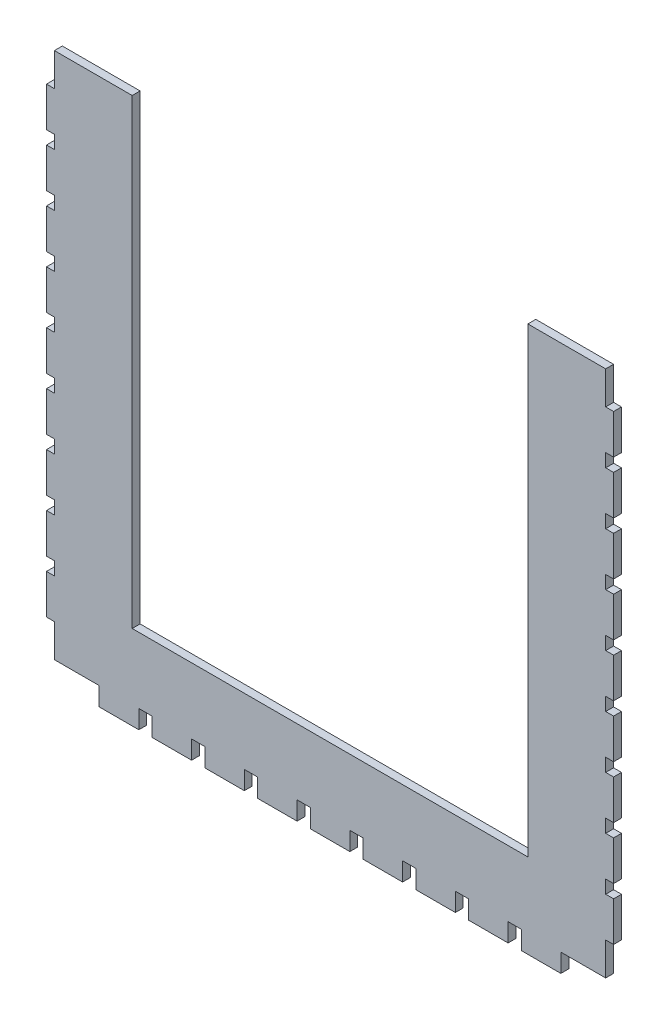
SolidWorks part; units mm, degrees
material "Nickel"
ref_plane "Front Plane" through (0, 0, 0) normal (0, 0, 1) x (1, 0, 0)
ref_plane "Top Plane" through (0, 0, 0) normal (0, 1, 0) x (1, 0, 0)
ref_plane "Right Plane" through (0, 0, 0) normal (1, 0, 0) x (0, 0, -1)
sketch "Sketch1" plane through (0, 0, 0) normal (0, 0, 1) x (1, 0, 0)
  line L0 (-104.5, 100) -> (-104.5, -100)
  line L3 (-104.5, 100) -> (104.5, 100)
  line L4 (104.5, -100) -> (104.5, 100)
  line L5 (-104.5, -100) -> (104.5, -100)
  line L6 (0, 100) -> (0, -100) construction
  line L7 (-104.5, 0) -> (104.5, 0) construction
  line L8 (107.5, 0) -> (104.5, 0) construction
  line L9 (-75, 100) -> (75, 100)
  line L10 (-75, 100) -> (-75, -75)
  line L11 (-75, -75) -> (75, -75)
  line L12 (75, 100) -> (75, -75)
  line L15 (104.5, 7.5) -> (107.5, 7.5)
  line L16 (104.5, 7.5) -> (104.5, -7.5)
  line L17 (104.5, -7.5) -> (107.5, -7.5)
  line L18 (107.5, 7.5) -> (107.5, -7.5)
  line L19 (106, 7.5) -> (106, -7.5) construction
  line L20 (104.5, -12.5) -> (104.5, -27.5)
  line L21 (104.5, -12.5) -> (107.5, -12.5)
  line L22 (107.5, -12.5) -> (107.5, -27.5)
  line L23 (104.5, -27.5) -> (107.5, -27.5)
  line L24 (104.5, -32.5) -> (104.5, -47.5)
  line L25 (104.5, -32.5) -> (107.5, -32.5)
  line L26 (107.5, -32.5) -> (107.5, -47.5)
  line L27 (104.5, -47.5) -> (107.5, -47.5)
  line L28 (104.5, -52.5) -> (104.5, -67.5)
  line L29 (104.5, -52.5) -> (107.5, -52.5)
  line L30 (107.5, -52.5) -> (107.5, -67.5)
  line L31 (104.5, -67.5) -> (107.5, -67.5)
  line L32 (104.5, -72.5) -> (104.5, -87.5)
  line L33 (104.5, -72.5) -> (107.5, -72.5)
  line L34 (107.5, -72.5) -> (107.5, -87.5)
  line L35 (104.5, -87.5) -> (107.5, -87.5)
  line L36 (104.5, 27.5) -> (104.5, 12.5)
  line L37 (104.5, 27.5) -> (107.5, 27.5)
  line L38 (107.5, 27.5) -> (107.5, 12.5)
  line L39 (104.5, 12.5) -> (107.5, 12.5)
  line L40 (104.5, 47.5) -> (104.5, 32.5)
  line L41 (104.5, 47.5) -> (107.5, 47.5)
  line L42 (107.5, 47.5) -> (107.5, 32.5)
  line L43 (104.5, 32.5) -> (107.5, 32.5)
  line L44 (104.5, 67.5) -> (104.5, 52.5)
  line L45 (104.5, 67.5) -> (107.5, 67.5)
  line L46 (107.5, 67.5) -> (107.5, 52.5)
  line L47 (104.5, 52.5) -> (107.5, 52.5)
  line L48 (104.5, 87.5) -> (104.5, 72.5)
  line L49 (104.5, 87.5) -> (107.5, 87.5)
  line L50 (107.5, 87.5) -> (107.5, 72.5)
  line L51 (104.5, 72.5) -> (107.5, 72.5)
  line L52 (-104.5, -32.5) -> (-107.5, -32.5)
  line L53 (-107.5, -32.5) -> (-107.5, -47.5)
  line L54 (-104.5, -47.5) -> (-107.5, -47.5)
  line L55 (-104.5, -32.5) -> (-104.5, -47.5)
  line L56 (-104.5, -52.5) -> (-107.5, -52.5)
  line L57 (-107.5, -52.5) -> (-107.5, -67.5)
  line L58 (-104.5, -67.5) -> (-107.5, -67.5)
  line L59 (-104.5, -52.5) -> (-104.5, -67.5)
  line L60 (-104.5, 87.5) -> (-107.5, 87.5)
  line L61 (-107.5, 87.5) -> (-107.5, 72.5)
  line L62 (-104.5, 72.5) -> (-107.5, 72.5)
  line L63 (-104.5, 87.5) -> (-104.5, 72.5)
  line L64 (-104.5, 67.5) -> (-107.5, 67.5)
  line L65 (-107.5, 67.5) -> (-107.5, 52.5)
  line L66 (-104.5, 52.5) -> (-107.5, 52.5)
  line L67 (-104.5, 67.5) -> (-104.5, 52.5)
  line L68 (-104.5, 47.5) -> (-107.5, 47.5)
  line L69 (-107.5, 47.5) -> (-107.5, 32.5)
  line L70 (-104.5, 32.5) -> (-107.5, 32.5)
  line L71 (-104.5, 47.5) -> (-104.5, 32.5)
  line L72 (-104.5, 27.5) -> (-107.5, 27.5)
  line L73 (-107.5, 27.5) -> (-107.5, 12.5)
  line L74 (-104.5, 12.5) -> (-107.5, 12.5)
  line L75 (-104.5, 27.5) -> (-104.5, 12.5)
  line L76 (-104.5, -12.5) -> (-107.5, -12.5)
  line L77 (-107.5, -12.5) -> (-107.5, -27.5)
  line L78 (-104.5, -27.5) -> (-107.5, -27.5)
  line L79 (-104.5, -12.5) -> (-104.5, -27.5)
  line L80 (-104.5, -7.5) -> (-107.5, -7.5)
  line L81 (-107.5, 7.5) -> (-107.5, -7.5)
  line L82 (-104.5, 7.5) -> (-107.5, 7.5)
  line L83 (-104.5, 7.5) -> (-104.5, -7.5)
  line L84 (-104.5, -87.5) -> (-107.5, -87.5)
  line L85 (-107.5, -72.5) -> (-107.5, -87.5)
  line L86 (-104.5, -72.5) -> (-107.5, -72.5)
  line L87 (-104.5, -72.5) -> (-104.5, -87.5)
  line L88 (0, -100) -> (0, -107) construction
  line L89 (-7.5, -100) -> (7.5, -100)
  line L90 (-7.5, -100) -> (-7.5, -107)
  line L91 (-7.5, -107) -> (7.5, -107)
  line L92 (7.5, -100) -> (7.5, -107)
  line L93 (12.5, -100) -> (12.5, -107)
  line L94 (-7.5, -103.5) -> (7.5, -103.5) construction
  line L95 (12.5, -100) -> (27.5, -100)
  line L96 (27.5, -100) -> (27.5, -107)
  line L97 (12.5, -107) -> (27.5, -107)
  line L98 (32.5, -100) -> (32.5, -107)
  line L99 (32.5, -100) -> (47.5, -100)
  line L100 (47.5, -100) -> (47.5, -107)
  line L101 (32.5, -107) -> (47.5, -107)
  line L102 (52.5, -100) -> (52.5, -107)
  line L103 (52.5, -100) -> (67.5, -100)
  line L104 (67.5, -100) -> (67.5, -107)
  line L105 (52.5, -107) -> (67.5, -107)
  line L106 (72.5, -100) -> (72.5, -107)
  line L107 (72.5, -100) -> (87.5, -100)
  line L108 (87.5, -100) -> (87.5, -107)
  line L109 (72.5, -107) -> (87.5, -107)
  line L110 (-7.5, -100) -> (-7.5, -107)
  line L111 (-7.5, -100) -> (7.5, -100)
  line L112 (7.5, -100) -> (7.5, -107)
  line L113 (-7.5, -107) -> (7.5, -107)
  line L114 (12.5, -100) -> (12.5, -107)
  line L115 (12.5, -100) -> (27.5, -100)
  line L116 (27.5, -100) -> (27.5, -107)
  line L117 (12.5, -107) -> (27.5, -107)
  line L118 (32.5, -100) -> (32.5, -107)
  line L119 (32.5, -100) -> (47.5, -100)
  line L120 (47.5, -100) -> (47.5, -107)
  line L121 (32.5, -107) -> (47.5, -107)
  line L122 (52.5, -100) -> (52.5, -107)
  line L123 (52.5, -100) -> (67.5, -100)
  line L124 (67.5, -100) -> (67.5, -107)
  line L125 (52.5, -107) -> (67.5, -107)
  line L126 (-27.5, -100) -> (-27.5, -107)
  line L127 (-27.5, -100) -> (-12.5, -100)
  line L128 (-12.5, -100) -> (-12.5, -107)
  line L129 (-27.5, -107) -> (-12.5, -107)
  line L130 (-7.5, -100) -> (-7.5, -107)
  line L131 (-7.5, -100) -> (7.5, -100)
  line L132 (7.5, -100) -> (7.5, -107)
  line L133 (-7.5, -107) -> (7.5, -107)
  line L134 (12.5, -100) -> (12.5, -107)
  line L135 (12.5, -100) -> (27.5, -100)
  line L136 (27.5, -100) -> (27.5, -107)
  line L137 (12.5, -107) -> (27.5, -107)
  line L138 (32.5, -100) -> (32.5, -107)
  line L139 (32.5, -100) -> (47.5, -100)
  line L140 (47.5, -100) -> (47.5, -107)
  line L141 (32.5, -107) -> (47.5, -107)
  line L142 (-47.5, -100) -> (-47.5, -107)
  line L143 (-47.5, -100) -> (-32.5, -100)
  line L144 (-32.5, -100) -> (-32.5, -107)
  line L145 (-47.5, -107) -> (-32.5, -107)
  line L146 (-27.5, -100) -> (-27.5, -107)
  line L147 (-27.5, -100) -> (-12.5, -100)
  line L148 (-12.5, -100) -> (-12.5, -107)
  line L149 (-27.5, -107) -> (-12.5, -107)
  line L150 (-7.5, -100) -> (-7.5, -107)
  line L151 (-7.5, -100) -> (7.5, -100)
  line L152 (7.5, -100) -> (7.5, -107)
  line L153 (-7.5, -107) -> (7.5, -107)
  line L154 (12.5, -100) -> (12.5, -107)
  line L155 (12.5, -100) -> (27.5, -100)
  line L156 (27.5, -100) -> (27.5, -107)
  line L157 (12.5, -107) -> (27.5, -107)
  line L158 (-67.5, -100) -> (-67.5, -107)
  line L159 (-67.5, -100) -> (-52.5, -100)
  line L160 (-52.5, -100) -> (-52.5, -107)
  line L161 (-67.5, -107) -> (-52.5, -107)
  line L162 (-47.5, -100) -> (-47.5, -107)
  line L163 (-47.5, -100) -> (-32.5, -100)
  line L164 (-32.5, -100) -> (-32.5, -107)
  line L165 (-47.5, -107) -> (-32.5, -107)
  line L166 (-27.5, -100) -> (-27.5, -107)
  line L167 (-27.5, -100) -> (-12.5, -100)
  line L168 (-12.5, -100) -> (-12.5, -107)
  line L169 (-27.5, -107) -> (-12.5, -107)
  line L170 (-7.5, -100) -> (-7.5, -107)
  line L171 (-7.5, -100) -> (7.5, -100)
  line L172 (7.5, -100) -> (7.5, -107)
  line L173 (-7.5, -107) -> (7.5, -107)
  line L174 (-27.5, -100) -> (-27.5, -107)
  line L175 (-27.5, -100) -> (-12.5, -100)
  line L176 (-12.5, -100) -> (-12.5, -107)
  line L177 (-27.5, -107) -> (-12.5, -107)
  line L178 (-47.5, -100) -> (-47.5, -107)
  line L179 (-47.5, -100) -> (-32.5, -100)
  line L180 (-32.5, -100) -> (-32.5, -107)
  line L181 (-47.5, -107) -> (-32.5, -107)
  line L182 (-67.5, -100) -> (-67.5, -107)
  line L183 (-67.5, -100) -> (-52.5, -100)
  line L184 (-52.5, -100) -> (-52.5, -107)
  line L185 (-67.5, -107) -> (-52.5, -107)
  line L186 (-87.5, -100) -> (-87.5, -107)
  line L187 (-87.5, -100) -> (-72.5, -100)
  line L188 (-72.5, -100) -> (-72.5, -107)
  line L189 (-87.5, -107) -> (-72.5, -107)
  point P0 (0, 0)
  point P11 (0, 0)
  point P12 (0, 0)
  point P21 (106, 12.5)
  dimension "D1" = 200
  dimension "D2" = 209
  dimension "D3" = 75
  dimension "D4" = 150
  dimension "D5" = 3
  dimension "D6" = 15
  dimension "D9" = 5
  dimension "D10" = 5
  dimension "D11" = 15
  dimension "D12" = 7
  dimension "D15" = 5
  dimension "D16" = 5
  dimension "D17" = 100
  dimension "D18" = 75
  dimension "D7" = 5
  dimension "D8" = 5
  dimension "D13" = 5
  dimension "D14" = 5
extrude "Boss-Extrude1" add sketch "Sketch1" along normal blind 3 contours L0 L5 L4 | L186 L189 L188 L5 | L158 L161 L160 L5 | L142 L145 L144 L5 | L126 L129 L128 L5 | L92 L5 L90 L91 | L93 L97 L96 L5 | L98 L101 L100 L5 | L106 L109 L108 L5 | L4 L35 L34 L33 | L4 L31 L30 L29 | L4 L27 L26 L25 | L4 L23 L22 L21 | L4 L39 L38 L37 | L4 L47 L46 L45 | L4 L51 L50 L49 | L62 L0 L60 L61 | L66 L0 L64 L65 | L70 L0 L68 L69 | L74 L0 L72 L73 | L0 L82 L81 L80 | L78 L0 L76 L77 | L54 L0 L52 L53 | L58 L0 L56 L57 | L0 L86 L85 L84 | L42 L43 L40 L41 | L102 L105 L104 L103 | L16 L15 L18 L17
sketch "Sketch3" plane through (0, -75, 0) normal (0, 1, 0) x (1, 0, 0)
  line L1 (-75, -3) -> (75, -3)
  line L2 (-75, -3) -> (-75, 0)
  line L3 (-75, 0) -> (75, 0)
  line L4 (75, -3) -> (75, 0)
extrude "Boss-Extrude2" [suppressed] add sketch "Sketch3" along normal blind 150
sketch "Sketch5" [suppressed] plane through (0, 0, 3) normal (0, 0, 1) x (1, 0, 0)
  line L0 (0, 0) -> (0, -80.2869) construction
  line L6 (0, -14.4991) -> (12.5, -7.1524)
  line L7 (12.5, -7.1524) -> (12.5, 6.8326)
  line L8 (12.5, 6.8326) -> (0, 14.8505)
  line L9 (0, 14.8505) -> (-12.5, 6.8326)
  line L10 (-12.5, 6.8326) -> (-12.5, -7.1524)
  line L11 (-12.5, -7.1524) -> (0, -14.4991)
  line L12 (-17.5, 11.8326) -> (-5, 19.1793)
  line L13 (-5, 19.1793) -> (-5, 33.1643)
  line L14 (-5, 33.1643) -> (-17.5, 41.1822)
  line L15 (-17.5, 41.1822) -> (-30, 33.1643)
  line L16 (-30, 33.1643) -> (-30, 19.1793)
  line L17 (-30, 19.1793) -> (-17.5, 11.8326)
  line L18 (17.5, 11.8326) -> (30, 19.1793)
  line L19 (30, 19.1793) -> (30, 33.1643)
  line L20 (30, 33.1643) -> (17.5, 41.1822)
  line L21 (17.5, 41.1822) -> (5, 33.1643)
  line L22 (5, 33.1643) -> (5, 19.1793)
  line L23 (5, 19.1793) -> (17.5, 11.8326)
  line L24 (-35, 38.1643) -> (-22.5, 45.511)
  line L25 (-22.5, 45.511) -> (-22.5, 59.496)
  line L26 (-22.5, 59.496) -> (-35, 67.5139)
  line L27 (-35, 67.5139) -> (-47.5, 59.496)
  line L28 (-47.5, 59.496) -> (-47.5, 45.511)
  line L29 (-47.5, 45.511) -> (-35, 38.1643)
  line L30 (0, 38.1643) -> (12.5, 45.511)
  line L31 (12.5, 45.511) -> (12.5, 59.496)
  line L32 (12.5, 59.496) -> (0, 67.5139)
  line L33 (0, 67.5139) -> (-12.5, 59.496)
  line L34 (-12.5, 59.496) -> (-12.5, 45.511)
  line L35 (-12.5, 45.511) -> (0, 38.1643)
  line L36 (35, 38.1643) -> (47.5, 45.511)
  line L37 (47.5, 45.511) -> (47.5, 59.496)
  line L38 (47.5, 59.496) -> (35, 67.5139)
  line L39 (35, 67.5139) -> (22.5, 59.496)
  line L40 (22.5, 59.496) -> (22.5, 45.511)
  line L41 (22.5, 45.511) -> (35, 38.1643)
  line L42 (-90, 0) -> (90, 0) construction
  line L43 (0, 0) -> (0, 84.5664) construction
  line L44 (-107.5, -72.5) -> (-107.5, -87.5) construction
  line L45 (90, 26.3317) -> (-90, 26.3317) construction
  line L46 (-87.5, -107) -> (-72.5, -107) construction
  line L47 (-17.5, -41.1506) -> (-5, -33.8039)
  line L48 (-5, -33.8039) -> (-5, -19.4991)
  line L49 (-5, -19.4991) -> (-17.5, -12.1524)
  line L50 (-17.5, -12.1524) -> (-30, -19.4991)
  line L51 (-30, -19.4991) -> (-30, -33.8039)
  line L52 (-30, -33.8039) -> (-17.5, -41.1506)
  line L53 (17.5, -41.1506) -> (30, -33.8039)
  line L54 (30, -33.8039) -> (30, -19.4991)
  line L55 (30, -19.4991) -> (17.5, -12.1524)
  line L56 (17.5, -12.1524) -> (5, -19.4991)
  line L57 (5, -19.4991) -> (5, -33.8039)
  line L58 (5, -33.8039) -> (17.5, -41.1506)
  line L59 (-35, -67.8021) -> (-22.5, -60.4554)
  line L60 (-22.5, -60.4554) -> (-22.5, -46.1506)
  line L61 (-22.5, -46.1506) -> (-35, -38.8039)
  line L62 (-35, -38.8039) -> (-47.5, -46.1506)
  line L63 (-47.5, -46.1506) -> (-47.5, -60.4554)
  line L64 (-47.5, -60.4554) -> (-35, -67.8021)
  line L65 (0, -67.8021) -> (12.5, -60.4554)
  line L66 (12.5, -60.4554) -> (12.5, -46.1506)
  line L67 (12.5, -46.1506) -> (0, -38.8039)
  line L68 (0, -38.8039) -> (-12.5, -46.1506)
  line L69 (-12.5, -46.1506) -> (-12.5, -60.4554)
  line L70 (-12.5, -60.4554) -> (0, -67.8021)
  line L71 (35, -67.8021) -> (47.5, -60.4554)
  line L72 (47.5, -60.4554) -> (47.5, -46.1506)
  line L73 (47.5, -46.1506) -> (35, -38.8039)
  line L74 (35, -38.8039) -> (22.5, -46.1506)
  line L75 (22.5, -46.1506) -> (22.5, -60.4554)
  line L76 (22.5, -60.4554) -> (35, -67.8021)
  line L77 (35, -14.4991) -> (47.5, -7.1524)
  line L78 (47.5, -7.1524) -> (47.5, 7.1524)
  line L79 (47.5, 7.1524) -> (35, 14.4991)
  line L80 (35, 14.4991) -> (22.5, 7.1524)
  line L81 (22.5, 7.1524) -> (22.5, -7.1524)
  line L82 (22.5, -7.1524) -> (35, -14.4991)
  line L83 (-35, -14.4991) -> (-22.5, -7.1524)
  line L84 (-22.5, -7.1524) -> (-22.5, 7.1524)
  line L85 (-22.5, 7.1524) -> (-35, 14.4991)
  line L86 (-35, 14.4991) -> (-47.5, 7.1524)
  line L87 (-47.5, 7.1524) -> (-47.5, -7.1524)
  line L88 (-47.5, -7.1524) -> (-35, -14.4991)
  line L89 (-17.5, -94.4537) -> (-5, -87.1069)
  line L90 (-5, -87.1069) -> (-5, -72.8021)
  line L91 (-5, -72.8021) -> (-17.5, -65.4554)
  line L92 (-17.5, -65.4554) -> (-30, -72.8021)
  line L93 (-30, -72.8021) -> (-30, -87.1069)
  line L94 (-30, -87.1069) -> (-17.5, -94.4537)
  line L95 (17.5, -94.4537) -> (30, -87.1069)
  line L96 (30, -87.1069) -> (30, -72.8021)
  line L97 (30, -72.8021) -> (17.5, -65.4554)
  line L98 (17.5, -65.4554) -> (5, -72.8021)
  line L99 (5, -72.8021) -> (5, -87.1069)
  line L100 (5, -87.1069) -> (17.5, -94.4537)
  circle A0 centre (0, 0) radius 12.5 construction
  circle A1 centre (-17.5, 26.3317) radius 12.5 construction
  circle A2 centre (17.5, 26.3317) radius 12.5 construction
  circle A3 centre (-35, 52.6634) radius 12.5 construction
  circle A4 centre (0, 52.6634) radius 12.5 construction
  circle A5 centre (35, 52.6634) radius 12.5 construction
  circle A6 centre (-17.5, -26.6515) radius 12.5 construction
  circle A7 centre (17.5, -26.6515) radius 12.5 construction
  circle A8 centre (-35, -53.303) radius 12.5 construction
  circle A9 centre (0, -53.303) radius 12.5 construction
  circle A10 centre (35, -53.303) radius 12.5 construction
  circle A11 centre (35, 0) radius 12.5 construction
  circle A12 centre (-35, 0) radius 12.5 construction
  circle A13 centre (-17.5, -79.9545) radius 12.5 construction
  circle A14 centre (17.5, -79.9545) radius 12.5 construction
  dimension "D11" = 25
  dimension "D12" = 25
  dimension "D13" = 25
  dimension "D14" = 25
  dimension "D15" = 25
  dimension "D16" = 26.3317
  dimension "D23" = 25
  dimension "D24" = 25
  dimension "D25" = 25
  dimension "D26" = 25
  dimension "D27" = 25
  dimension "D29" = 25
  dimension "D30" = 25
  dimension "D31" = 25
  dimension "D32" = 25
  dimension "D4" = 5
  dimension "D5" = 5
  dimension "D6" = 5
  dimension "D7" = 5
  dimension "D8" = 5
  dimension "D9" = 5
  dimension "D10" = 5
  dimension "D17" = 35
  dimension "D18" = 34.5
  dimension "D19" = 23.6652
  dimension "D22" = 5
  dimension "D28" = 5
  dimension "D33" = 5
extrude "Cut-Extrude1" [suppressed] cut sketch "Sketch5" against normal through all
